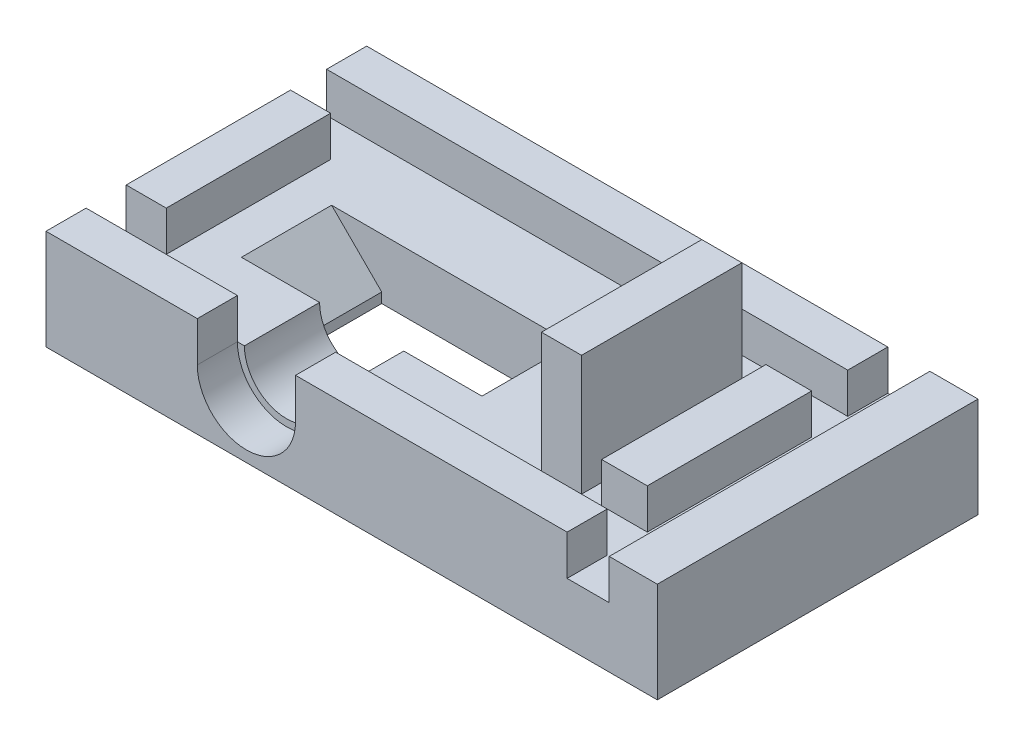
SolidWorks part; units mm, degrees
ref_plane "Ebene vorne" through (0, 0, 0) normal (0, 0, 1) x (1, 0, 0)
ref_plane "Ebene oben" through (0, 0, 0) normal (0, 1, 0) x (1, 0, 0)
ref_plane "Ebene rechts" through (0, 0, 0) normal (1, 0, 0) x (0, 0, -1)
sketch "Sketch1" plane through (0, 0, 0) normal (0, 1, 0) x (1, 0, 0)
  line L1 (-15.25, 8) -> (15.25, 8)
  line L2 (-15.25, 8) -> (-15.25, -8)
  line L3 (-15.25, -8) -> (15.25, -8)
  line L4 (15.25, 8) -> (15.25, -8)
  line L5 (-15.25, 8) -> (15.25, -8) construction
  line L6 (-15.25, -8) -> (15.25, 8) construction
  point P0 (0, 0)
  dimension "D1" = 16
  dimension "D2" = 30.5
extrude "Boss-Extrude1" add sketch "Sketch1" along normal blind 2 and the other way blind 1
sketch "Sketch2" plane through (0, 2, 0) normal (0, 1, 0) x (1, 0, 0)
  line L0 (12.85, 8) -> (12.85, -8)
  line L1 (-15.25, 8) -> (10.75, 8)
  line L2 (-15.25, 8) -> (-15.25, 6)
  line L3 (-15.25, -8) -> (10.75, -8)
  line L4 (15.25, 8) -> (15.25, -8)
  line L5 (-15.25, -6) -> (-15.25, -8)
  line L6 (-15.25, 4.2) -> (-15.25, -4)
  line L7 (-15.25, -6) -> (10.75, -6)
  line L8 (10.75, -6) -> (10.75, -8)
  line L9 (-15.25, 6) -> (10.75, 6)
  line L10 (10.75, 6) -> (10.75, 8)
  line L11 (-13.25, 4.2) -> (-13.25, -4)
  line L12 (-13.25, 4.2) -> (-15.25, 4.2)
  line L13 (-13.25, -4) -> (-15.25, -4)
  line L14 (12.85, 8) -> (15.25, 8)
  line L15 (8.4703, 4.2) -> (8.4703, -4)
  line L16 (8.4703, 4.2) -> (10.75, 4.2)
  line L17 (8.4703, -4) -> (10.75, -4)
  line L18 (10.75, 4.2) -> (10.75, -4)
  line L20 (12.85, -8) -> (15.25, -8)
  point P0 (0, 0)
  dimension "D1" = 2.4
  dimension "D2" = 26
  dimension "D3" = 2
  dimension "D4" = 2.1
  dimension "D5" = 2
  dimension "D6" = 8.2
  dimension "D7" = 2
extrude "Boss-Extrude2" add sketch "Sketch2" along normal blind 2
sketch "Sketch3" plane through (0, 2, 0) normal (0, 1, 0) x (1, 0, 0)
  line L0 (7.4703, 4) -> (5.4703, 4)
  line L1 (5.4703, 4) -> (5.4703, -4)
  line L2 (5.4703, -4) -> (7.4703, -4)
  line L3 (7.4703, 4) -> (7.4703, -4)
  dimension "D1" = 8
  dimension "D3" = 2
extrude "Boss-Extrude3" add sketch "Sketch3" along normal blind 6
sketch "Sketch4" plane through (0, 2, 0) normal (0, 1, 0) x (1, 0, 0)
  line L0 (-15.25, 4.2) -> (-15.25, -4) construction
  line L2 (-1.75, 0) -> (0, 0) construction
  line L3 (-8.75, 2.25) -> (-1.75, 2.25)
  line L4 (-8.75, 2.25) -> (-8.75, -2.25)
  line L5 (-8.75, -2.25) -> (-1.75, -2.25)
  line L6 (-1.75, 2.25) -> (-1.75, -2.25)
  line L7 (-8.75, 2.25) -> (-1.75, -2.25) construction
  line L8 (-8.75, -2.25) -> (-1.75, 2.25) construction
  dimension "D1" = 6.5
  dimension "D2" = 4.5
  dimension "D3" = 7
extrude "Cut-Extrude1" cut sketch "Sketch4" against normal blind 3
sketch "Sketch5" plane through (0, 0, 8) normal (0, 0, -1) x (-1, 0, 0)
  line L0 (15.25, 4) -> (5.25, 4) construction
  line L1 (-10.75, 4) -> (15.25, 4) construction
  line L2 (5.25, 4) -> (5.25, 2) construction
  line L3 (-10.75, 2) -> (3.25, 2) construction
  line L5 (-15.25, -1) -> (15.25, -1) construction
  line L7 (3.15, 2) -> (3.15, 4.2)
  line L8 (3.15, 4.2) -> (7.35, 4.2)
  line L9 (7.35, 2) -> (7.35, 4.2)
  arc A0 (3.15, 2) -> (7.35, 2) centre (5.25, 2) ccw
  dimension "D3" = 4.2
  dimension "D4" = 2.2
  dimension "D1" = 10
  dimension "D2" = 3
extrude "Cut-Extrude2" cut sketch "Sketch5" along normal blind 7
sketch "Sketch6" plane through (0, 0, 8) normal (0, 0, 1) x (1, 0, 0)
  line L0 (-7.7, 4) -> (-7.7, 2)
  line L3 (-3.15, 4) -> (10.75, 4) construction
  line L4 (-3, 4) -> (-7.5, 4)
  line L5 (-15.25, 4) -> (-7.35, 4) construction
  line L7 (-2.8, 2) -> (-2.8, 4)
  line L9 (-7.7, 4) -> (-7.5, 4)
  line L10 (-3, 4) -> (-2.8, 4)
  line L12 (-7.7, 4.2) -> (-7.7, 2) construction
  line L13 (-2.8, 4.2) -> (-7.7, 4.2) construction
  line L14 (-2.8, 2) -> (-2.8, 4.2) construction
  line L15 (-3, 2) -> (-3, 4) construction
  line L16 (-7.5, 4) -> (-7.5, 2) construction
  arc A2 (-7.7, 2) -> (-2.8, 2) centre (-5.25, 2) ccw
  arc A3 (-7.5, 2) -> (-3, 2) centre (-5.25, 2) ccw construction
  dimension "D2" = 0.2
extrude "Cut-Extrude3" cut sketch "Sketch6" against normal blind 2
chamfer "Chamfer1" distance 2.5 angle 45 2 edges at (-1.75, 2, 0) (-8.75, 2, 0)
